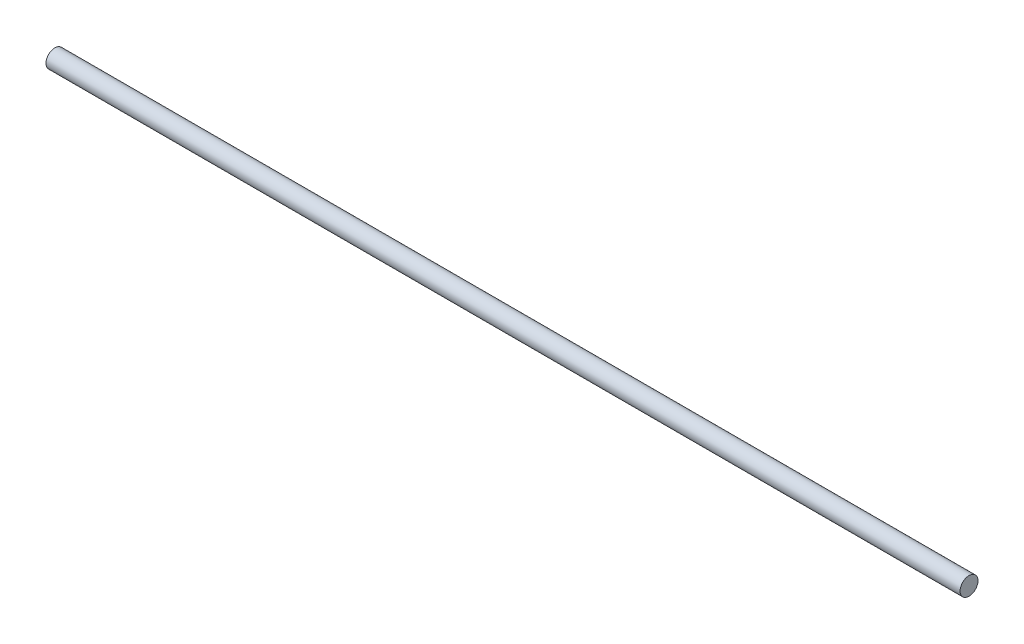
SolidWorks part; units mm, degrees
ref_plane "Front Plane" through (0, 0, 0) normal (0, 0, 1) x (1, 0, 0)
ref_plane "Top Plane" through (0, 0, 0) normal (0, 1, 0) x (1, 0, 0)
ref_plane "Right Plane" through (0, 0, 0) normal (1, 0, 0) x (0, 0, -1)
sketch "Sketch1" plane through (0, 0, 0) normal (1, 0, 0) x (0, 0, -1)
  circle A0 centre (0, 0) radius 5
  dimension "D1" = 10
extrude "Boss-Extrude1" add sketch "Sketch1" along normal blind 510
